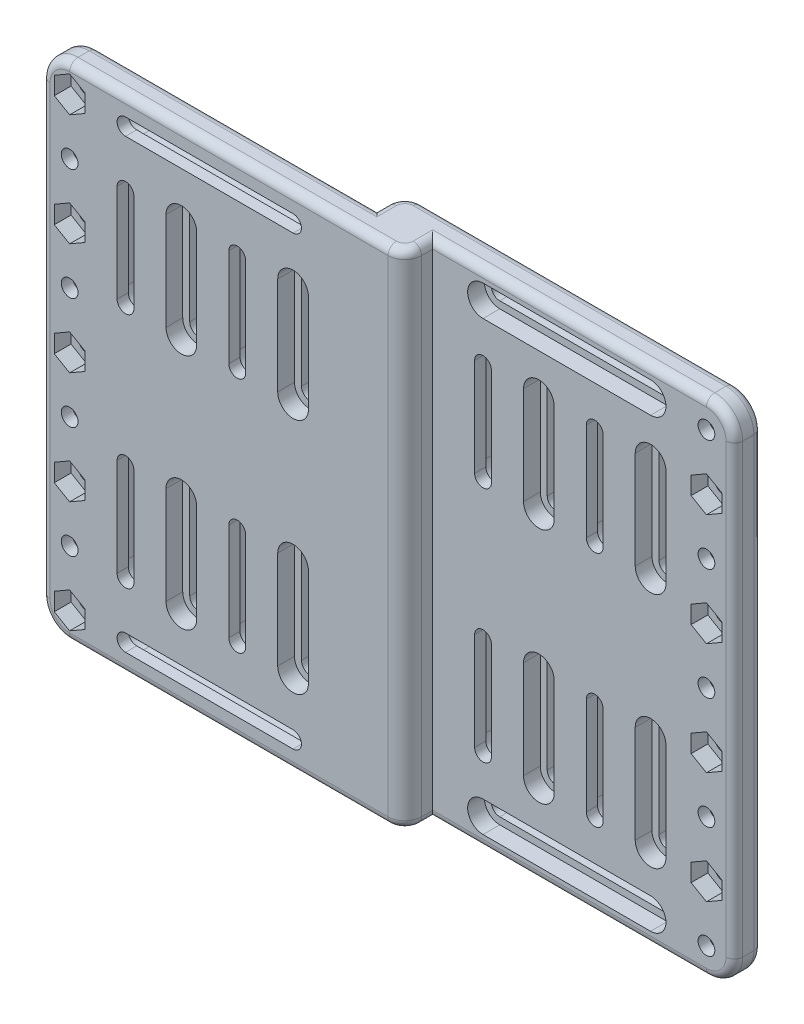
SolidWorks part; units mm, degrees
ref_plane "Front Plane" through (0, 0, 0) normal (0, 0, 1) x (1, 0, 0)
ref_plane "Top Plane" through (0, 0, 0) normal (0, 1, 0) x (1, 0, 0)
ref_plane "Right Plane" through (0, 0, 0) normal (1, 0, 0) x (0, 0, -1)
sketch "草图1" plane through (0, 0, 0) normal (0, 0, 1) x (1, 0, 0)
  line L2 (0, 45) -> (0, -45) construction
  circle A0 centre (0, 0) radius 45 construction
  dimension "D1" = 90
sketch "草图2" plane through (0, 0, 0) normal (0, 0, 1) x (1, 0, 0)
  line L0 (0, 45) -> (5, 45)
  line L1 (0, 45) -> (-60, 45)
  line L2 (0, 45) -> (0, -45) construction
  line L3 (0, -45) -> (-60, -45)
  line L4 (-60, 45) -> (-60, -45)
  line L5 (5, 45) -> (5, -45)
  line L6 (5, -45) -> (0, -45)
  dimension "D1" = 60
  dimension "D2" = 5
extrude "凸台-拉伸2" add sketch "草图2" along normal blind 5
sketch "草图3" plane through (0, 0, 0) normal (0, 0, -1) x (-1, 0, 0)
  line L0 (0, 45) -> (5, 45)
  line L1 (0, 45) -> (-59, 45)
  line L2 (0, 45) -> (0, -45) construction
  line L3 (0, -45) -> (-59, -45)
  line L4 (-59, 45) -> (-59, -45)
  line L5 (-5, 45) -> (60, 45) construction
  line L6 (5, 45) -> (5, -45)
  line L7 (60, -45) -> (-5, -45) construction
  line L8 (5, -45) -> (0, -45)
  dimension "D1" = 59
  dimension "D2" = 5
extrude "凸台-拉伸3" add sketch "草图3" along normal blind 5
sketch "草图4" plane through (0, 0, -5) normal (0, 0, -1) x (-1, 0, 0)
  line L0 (-59, 45) -> (-59, -45) construction
  circle A0 centre (-54, 0) radius 1.5
  dimension "D2" = 3
  dimension "D1" = 5
sketch "草图5" plane through (0, 0, -5) normal (0, 0, -1) x (-1, 0, 0)
  line L1 (-54, -3.1754) -> (-51.25, -1.5877)
  line L2 (-51.25, -1.5877) -> (-51.25, 1.5877)
  line L3 (-51.25, 1.5877) -> (-54, 3.1754)
  line L4 (-54, 3.1754) -> (-56.75, 1.5877)
  line L5 (-56.75, 1.5877) -> (-56.75, -1.5877)
  line L6 (-56.75, -1.5877) -> (-54, -3.1754)
  circle A1 centre (-54, 0) radius 2.75 construction
  dimension "D1" = 5.5
extrude "切除-拉伸1" cut sketch "草图4" against normal through all
extrude "切除-拉伸2" cut sketch "草图5" against normal blind 3
sketch "草图6" plane through (0, 0, 5) normal (0, 0, 1) x (1, 0, 0)
  line L0 (-60, 45) -> (-60, -45) construction
  circle A0 centre (-55, 0) radius 1.5
  dimension "D1" = 3
  dimension "D2" = 5
sketch "草图7" plane through (0, 0, 5) normal (0, 0, 1) x (1, 0, 0)
  line L1 (-55, 3.1754) -> (-57.75, 1.5877)
  line L2 (-57.75, 1.5877) -> (-57.75, -1.5877)
  line L3 (-57.75, -1.5877) -> (-55, -3.1754)
  line L4 (-55, -3.1754) -> (-52.25, -1.5877)
  line L5 (-52.25, -1.5877) -> (-52.25, 1.5877)
  line L6 (-52.25, 1.5877) -> (-55, 3.1754)
  circle A1 centre (-55, 0) radius 2.75 construction
  dimension "D1" = 5.5
extrude "切除-拉伸3" cut sketch "草图6" against normal through all
extrude "切除-拉伸4" cut sketch "草图7" against normal blind 3
pattern_linear "阵列(线性)1" count 5 spacing 10 along (0, -1, 0) count 5 spacing 10 along (0, 1, 0) of "切除-拉伸1"
pattern_linear "阵列(线性)2" count 5 spacing 10 along (0, -1, 0) count 5 spacing 10 along (0, 1, 0) of "切除-拉伸3"
pattern_linear "阵列(线性)9" count 3 spacing 20 along (0, 1, 0) count 3 spacing 20 along (0, -1, 0) of "切除-拉伸2"
pattern_linear "阵列(线性)10" count 3 spacing 20 along (0, 1, 0) count 3 spacing 20 along (0, -1, 0) of "切除-拉伸4"
sketch "草图19" plane through (0, 0, 0) normal (0, 0, 1) x (1, 0, 0)
  line L1 (54, 13.1754) -> (51.25, 11.5877)
  line L2 (51.25, 11.5877) -> (51.25, 8.4123)
  line L3 (51.25, 8.4123) -> (54, 6.8246)
  line L4 (54, 6.8246) -> (56.75, 8.4123)
  line L5 (56.75, 8.4123) -> (56.75, 11.5877)
  line L6 (56.75, 11.5877) -> (54, 13.1754)
  circle A0 centre (54, 10) radius 2.75 construction
  dimension "D1" = 5.5
extrude "切除-拉伸15" cut sketch "草图19" against normal blind 3
sketch "草图20" plane through (0, 0, 0) normal (0, 0, -1) x (-1, 0, 0)
  line L1 (55, 6.8246) -> (57.75, 8.4123)
  line L2 (57.75, 8.4123) -> (57.75, 11.5877)
  line L3 (57.75, 11.5877) -> (55, 13.1754)
  line L4 (55, 13.1754) -> (52.25, 11.5877)
  line L5 (52.25, 11.5877) -> (52.25, 8.4123)
  line L6 (52.25, 8.4123) -> (55, 6.8246)
  circle A0 centre (55, 10) radius 2.75 construction
  dimension "D1" = 5.5
extrude "切除-拉伸16" cut sketch "草图20" against normal blind 3
pattern_linear "阵列(线性)11" count 3 spacing 20 along (0, -1, 0) count 3 spacing 20 along (0, 1, 0) of "切除-拉伸15"
pattern_linear "阵列(线性)12" count 3 spacing 20 along (0, -1, 0) count 3 spacing 20 along (0, 1, 0) of "切除-拉伸16"
sketch "草图8" plane through (0, 0, 0) normal (0, 0, 1) x (1, 0, 0)
  line L0 (-45, -997.8304) -> (-45, 49002.1696) construction
  line L1 (45, -998.9875) -> (45, 49001.0125) construction
  line L2 (-1000, 0) -> (49000, 0) construction
  line L3 (0, 45) -> (0, -45) construction
  line L4 (0, -1000) -> (0, 49000) construction
  point P9 (0, 0)
  dimension "D1" = 90
  dimension "D2" = 45
sketch "草图9" plane through (0, 0, 0) normal (0, 0, -1) x (-1, 0, 0)
  line L0 (-1000, 0) -> (49000, 0) construction
  line L1 (0, 45) -> (0, -45) construction
  line L2 (15, 40) -> (45, 40) construction
  line L3 (15, 41.5) -> (45, 41.5)
  line L4 (15, 38.5) -> (45, 38.5)
  line L5 (15, -40) -> (45, -40) construction
  line L6 (15, -41.5) -> (45, -41.5)
  line L7 (15, -38.5) -> (45, -38.5)
  line L8 (60, 45) -> (60, -45) construction
  arc A0 (15, 41.5) -> (15, 38.5) centre (15, 40) ccw
  arc A1 (45, 38.5) -> (45, 41.5) centre (45, 40) ccw
  arc A2 (15, -41.5) -> (15, -38.5) centre (15, -40) cw
  arc A3 (45, -38.5) -> (45, -41.5) centre (45, -40) cw
  point P5 (0, 0)
  point P7 (30, 40)
  point P14 (30, -40)
  dimension "D1" = 3
  dimension "D2" = 15
  dimension "D3" = 30
  dimension "D4" = 80
sketch "草图10" plane through (0, 0, 0) normal (0, 0, 1) x (1, 0, 0)
  line L0 (-1015.4001, 0) -> (48984.5999, 0) construction
  line L2 (14, 40) -> (44, 40) construction
  line L3 (14, 41.5) -> (44, 41.5)
  line L4 (14, 38.5) -> (44, 38.5)
  line L5 (14, -40) -> (44, -40) construction
  line L6 (14, -41.5) -> (44, -41.5)
  line L7 (14, -38.5) -> (44, -38.5)
  line L9 (59, 45) -> (59, -45) construction
  arc A0 (14, 41.5) -> (14, 38.5) centre (14, 40) ccw
  arc A1 (44, 38.5) -> (44, 41.5) centre (44, 40) ccw
  arc A2 (14, -41.5) -> (14, -38.5) centre (14, -40) cw
  arc A3 (44, -38.5) -> (44, -41.5) centre (44, -40) cw
  point P7 (29, 40)
  point P14 (29, -40)
  dimension "D1" = 3
  dimension "D2" = 15
  dimension "D3" = 30
  dimension "D4" = 80
sketch "草图11" plane through (0, 0, 0) normal (0, 0, -1) x (-1, 0, 0)
  line L0 (15, 40) -> (45, 40) construction
  line L1 (15, 42.75) -> (45, 42.75)
  line L2 (15, 37.25) -> (45, 37.25)
  line L3 (15, -40) -> (45, -40) construction
  line L4 (15, -37.25) -> (45, -37.25)
  line L5 (15, -42.75) -> (45, -42.75)
  arc A0 (15, 42.75) -> (15, 37.25) centre (15, 40) ccw
  arc A1 (45, 37.25) -> (45, 42.75) centre (45, 40) ccw
  arc A2 (15, -37.25) -> (15, -42.75) centre (15, -40) ccw
  arc A3 (45, -42.75) -> (45, -37.25) centre (45, -40) ccw
  point P4 (30, 40)
  point P9 (30, -40)
  dimension "D1" = 5.5
  dimension "D2" = 5.5
sketch "草图12" plane through (0, 0, 0) normal (0, 0, 1) x (1, 0, 0)
  line L0 (14, 40) -> (44, 40) construction
  line L3 (14, 42.75) -> (44, 42.75)
  line L4 (14, 37.25) -> (44, 37.25)
  line L5 (14, -40) -> (44, -40) construction
  line L6 (14, -37.25) -> (44, -37.25)
  line L7 (14, -42.75) -> (44, -42.75)
  arc A3 (14, 42.75) -> (14, 37.25) centre (14, 40) ccw
  arc A4 (44, 37.25) -> (44, 42.75) centre (44, 40) ccw
  arc A5 (14, -37.25) -> (14, -42.75) centre (14, -40) ccw
  arc A6 (44, -42.75) -> (44, -37.25) centre (44, -40) ccw
  point P2 (29, 40)
  point P7 (29, -40)
  dimension "D1" = 5.5
  dimension "D2" = 5.5
extrude "切除-拉伸5" cut sketch "草图9" against normal through all
extrude "切除-拉伸6" cut sketch "草图11" against normal blind 3
extrude "切除-拉伸7" cut sketch "草图10" against normal through all
extrude "切除-拉伸8" cut sketch "草图12" against normal blind 3
sketch "草图13" plane through (0, 0, 0) normal (0, 0, -1) x (-1, 0, 0)
  line L0 (15, 30) -> (15, 12.5) construction
  line L1 (16.5, 30) -> (16.5, 12.5)
  line L2 (13.5, 30) -> (13.5, 12.5)
  line L3 (-1000, 0) -> (49000, 0) construction
  line L4 (15, -30) -> (15, -12.5) construction
  line L5 (16.5, -30) -> (16.5, -12.5)
  line L6 (13.5, -30) -> (13.5, -12.5)
  line L7 (15, 12.5) -> (15, -12.5) construction
  line L8 (60, 45) -> (60, -45) construction
  arc A0 (16.5, 30) -> (13.5, 30) centre (15, 30) ccw
  arc A1 (13.5, 12.5) -> (16.5, 12.5) centre (15, 12.5) ccw
  arc A2 (16.5, -30) -> (13.5, -30) centre (15, -30) cw
  arc A3 (13.5, -12.5) -> (16.5, -12.5) centre (15, -12.5) cw
  point P2 (15, 21.25)
  point P12 (15, -21.25)
  dimension "D1" = 3
  dimension "D2" = 25
  dimension "D3" = 60
  dimension "D4" = 45
sketch "草图14" plane through (0, 0, 0) normal (0, 0, 1) x (1, 0, 0)
  line L0 (-1000, 0) -> (49000, 0) construction
  line L2 (14, 12.5) -> (14, 30) construction
  line L3 (12.5, 12.5) -> (12.5, 30)
  line L4 (15.5, 12.5) -> (15.5, 30)
  line L5 (14, -12.5) -> (14, -30) construction
  line L6 (12.5, -12.5) -> (12.5, -30)
  line L7 (15.5, -12.5) -> (15.5, -30)
  line L8 (14, 12.5) -> (14, -12.5) construction
  line L9 (59, 45) -> (59, -45) construction
  arc A0 (12.5, 12.5) -> (15.5, 12.5) centre (14, 12.5) ccw
  arc A1 (15.5, 30) -> (12.5, 30) centre (14, 30) ccw
  arc A2 (12.5, -12.5) -> (15.5, -12.5) centre (14, -12.5) cw
  arc A3 (15.5, -30) -> (12.5, -30) centre (14, -30) cw
  point P5 (14, 21.25)
  point P12 (14, -21.25)
  dimension "D1" = 25
  dimension "D2" = 60
  dimension "D3" = 3
  dimension "D4" = 45
extrude "切除-拉伸9" cut sketch "草图13" against normal through all
extrude "切除-拉伸10" cut sketch "草图14" against normal through all
pattern_linear "阵列(线性)3" count 4 spacing 10 along (-1, 0, 0) of "切除-拉伸9"
pattern_linear "阵列(线性)4" count 4 spacing 10 along (1, 0, 0) of "切除-拉伸10"
sketch "草图15" plane through (0, 0, 0) normal (0, 0, -1) x (-1, 0, 0)
  line L0 (45, 30) -> (45, 12.5) construction
  line L1 (47.75, 30) -> (47.75, 12.5)
  line L2 (42.25, 30) -> (42.25, 12.5)
  line L3 (45, -12.5) -> (45, -30) construction
  line L4 (47.75, -12.5) -> (47.75, -30)
  line L5 (42.25, -12.5) -> (42.25, -30)
  arc A0 (47.75, 30) -> (42.25, 30) centre (45, 30) ccw
  arc A1 (42.25, 12.5) -> (47.75, 12.5) centre (45, 12.5) ccw
  arc A2 (47.75, -12.5) -> (42.25, -12.5) centre (45, -12.5) ccw
  arc A3 (42.25, -30) -> (47.75, -30) centre (45, -30) ccw
  point P4 (45, 21.25)
  point P9 (45, -21.25)
  dimension "D1" = 5.5
  dimension "D2" = 5.5
extrude "切除-拉伸11" cut sketch "草图15" against normal blind 3
sketch "草图16" plane through (0, 0, 5) normal (0, 0, 1) x (1, 0, 0)
  line L0 (-15, 30) -> (-15, 12.5) construction
  line L3 (-12.25, 30) -> (-12.25, 12.5)
  line L6 (-17.75, 30) -> (-17.75, 12.5)
  line L7 (-15, -12.5) -> (-15, -30) construction
  line L8 (-12.25, -12.5) -> (-12.25, -30)
  line L9 (-17.75, -12.5) -> (-17.75, -30)
  arc A4 (-12.25, 30) -> (-17.75, 30) centre (-15, 30) ccw
  arc A5 (-17.75, 12.5) -> (-12.25, 12.5) centre (-15, 12.5) ccw
  arc A6 (-12.25, -12.5) -> (-17.75, -12.5) centre (-15, -12.5) ccw
  arc A7 (-17.75, -30) -> (-12.25, -30) centre (-15, -30) ccw
  point P4 (-15, 21.25)
  point P9 (-15, -21.25)
  dimension "D1" = 5.5
  dimension "D2" = 5.5
extrude "切除-拉伸12" cut sketch "草图16" against normal blind 3
pattern_linear "阵列(线性)6" count 2 spacing 20 along (-1, 0, 0) of "切除-拉伸12"
pattern_linear "阵列(线性)13" count 2 spacing 20 along (1, 0, 0) of "切除-拉伸11"
sketch "草图17" plane through (0, 0, 0) normal (0, 0, 1) x (1, 0, 0)
  line L0 (44, 30) -> (44, 12.5) construction
  line L1 (46.75, 30) -> (46.75, 12.5)
  line L2 (41.25, 30) -> (41.25, 12.5)
  line L3 (44, -12.5) -> (44, -30) construction
  line L6 (46.75, -12.5) -> (46.75, -30)
  line L7 (41.25, -12.5) -> (41.25, -30)
  arc A0 (46.75, 30) -> (41.25, 30) centre (44, 30) ccw
  arc A1 (41.25, 12.5) -> (46.75, 12.5) centre (44, 12.5) ccw
  arc A4 (46.75, -12.5) -> (41.25, -12.5) centre (44, -12.5) ccw
  arc A5 (41.25, -30) -> (46.75, -30) centre (44, -30) ccw
  point P4 (44, 21.25)
  point P11 (44, -21.25)
  dimension "D1" = 5.5
  dimension "D2" = 5.5
extrude "切除-拉伸13" cut sketch "草图17" against normal blind 3
sketch "草图18" plane through (0, 0, -5) normal (0, 0, -1) x (-1, 0, 0)
  line L0 (-14, 30) -> (-14, 12.5) construction
  line L3 (-11.25, 30) -> (-11.25, 12.5)
  line L6 (-16.75, 30) -> (-16.75, 12.5)
  line L7 (-14, -12.5) -> (-14, -30) construction
  line L8 (-11.25, -12.5) -> (-11.25, -30)
  line L9 (-16.75, -12.5) -> (-16.75, -30)
  arc A4 (-11.25, 30) -> (-16.75, 30) centre (-14, 30) ccw
  arc A5 (-16.75, 12.5) -> (-11.25, 12.5) centre (-14, 12.5) ccw
  arc A6 (-11.25, -12.5) -> (-16.75, -12.5) centre (-14, -12.5) ccw
  arc A7 (-16.75, -30) -> (-11.25, -30) centre (-14, -30) ccw
  point P4 (-14, 21.25)
  point P9 (-14, -21.25)
  dimension "D1" = 5.5
  dimension "D2" = 5.5
extrude "切除-拉伸14" cut sketch "草图18" against normal blind 3
pattern_linear "阵列(线性)8" count 2 spacing 20 along (1, 0, 0) of "切除-拉伸14"
pattern_linear "阵列(线性)14" count 2 spacing 20 along (-1, 0, 0) of "切除-拉伸13"
fillet "圆角2" radius 3 2 edges at (-5, 0, -5) (5, 0, 5)
fillet "圆角3" radius 5 4 edges at (59, 45, -2.5) (-60, 45, 2.5) (-60, -45, 2.5) (59, -45, -2.5)
fillet "圆角4" radius 1.5 28 edges at (29.5, 45, 0) (57.5355, 43.5355, 0) (59, 0, 0) (57.5355, -43.5355, 0) (5, 45, 1) (4.1213, 45, 4.1213) (-26.5, 45, 5) (-58.5355, 43.5355, 5) (-60, 0, 5) (-58.5355, -43.5355, 5) (5, -45, 1) (4.1213, -45, 4.1213) (-30, 45, 0) (-58.5355, 43.5355, 0) (-60, 0, 0) (-58.5355, -43.5355, 0) (-5, 45, -1) (-4.1213, 45, -4.1213) (26, 45, -5) (57.5355, 43.5355, -5) (59, 0, -5) (57.5355, -43.5355, -5) (-5, -45, -1) (-4.1213, -45, -4.1213) (29.5, -45, 0) (-26.5, -45, 5) (-30, -45, 0) (26, -45, -5)
